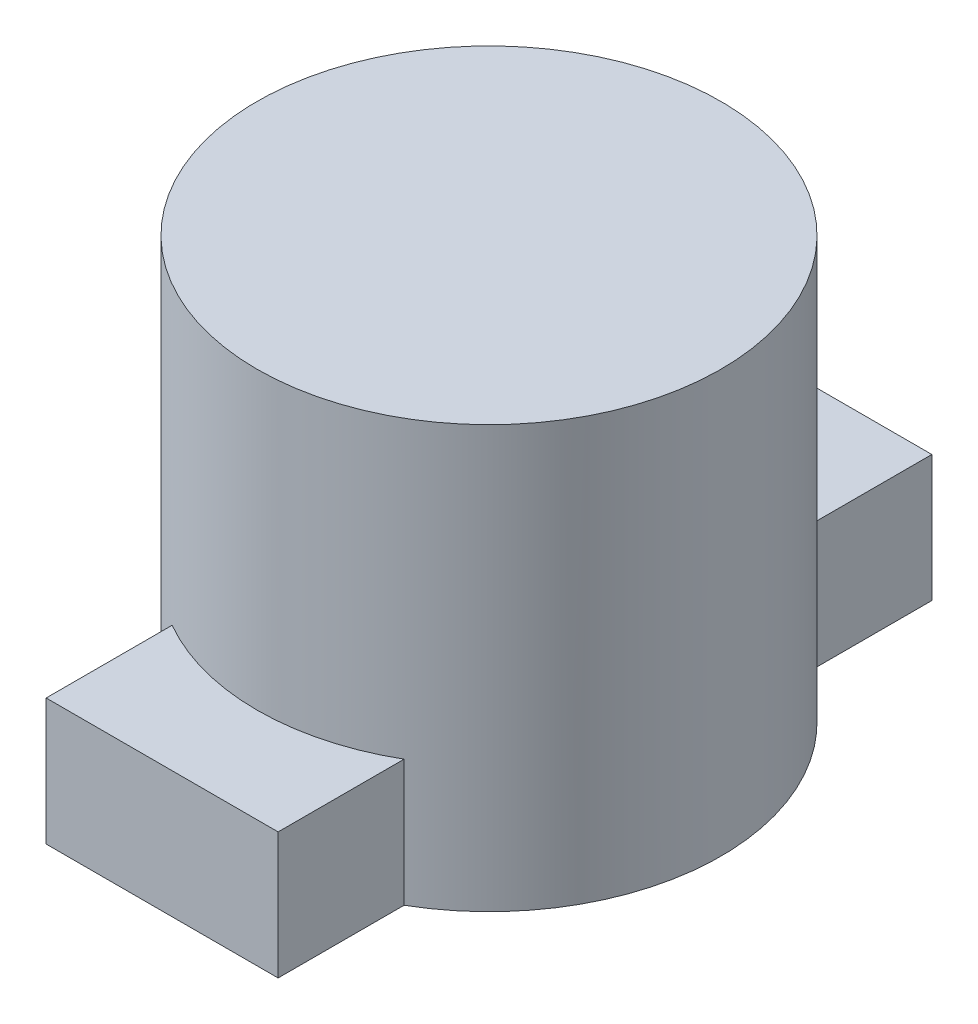
SolidWorks part; units mm, degrees
ref_plane "Alzado" through (0, 0, 0) normal (0, 0, 1) x (1, 0, 0)
ref_plane "Planta" through (0, 0, 0) normal (0, 1, 0) x (1, 0, 0)
ref_plane "Vista lateral" through (0, 0, 0) normal (1, 0, 0) x (0, 0, -1)
sketch "Croquis1" plane through (0, 0, 0) normal (0, 1, 0) x (1, 0, 0)
  line L1 (-9.6315, 1.4562) -> (-4.1315, 1.4562)
  line L2 (-9.6315, 1.4562) -> (-9.6315, -14.0438)
  line L3 (-9.6315, -14.0438) -> (-4.1315, -14.0438)
  line L4 (-4.1315, 1.4562) -> (-4.1315, -14.0438)
  circle A0 centre (-6.8815, -6.2938) radius 5.5
extrude "Saliente-Extruir1" add sketch "Croquis1" along normal blind 10 contours A0
sketch "Croquis3" plane through (0, 0, 0) normal (0, 1, 0) x (1, 0, 0)
  line L1 (-9.6315, 1.4562) -> (-4.1315, 1.4562)
  line L2 (-9.6315, 1.4562) -> (-9.6315, -14.0438)
  line L3 (-9.6315, -14.0438) -> (-4.1315, -14.0438)
  line L4 (-4.1315, 1.4562) -> (-4.1315, -14.0438)
extrude "Saliente-Extruir2" add sketch "Croquis3" along normal blind 3
